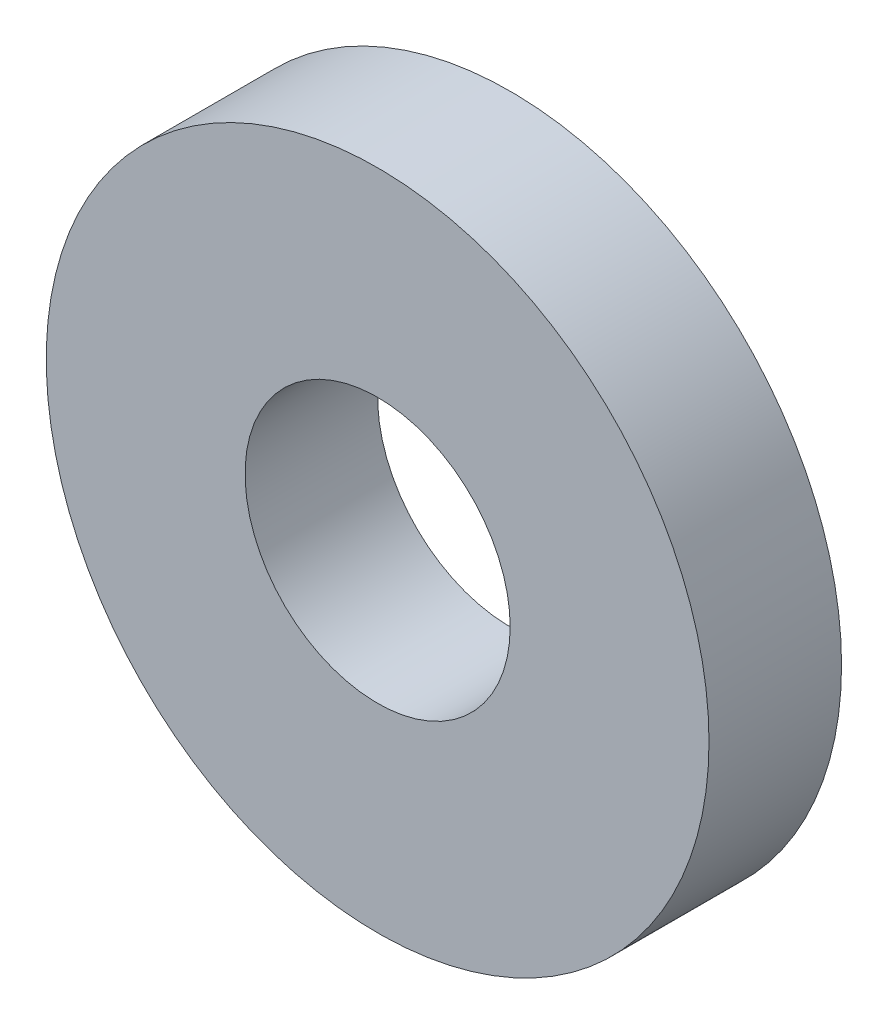
SolidWorks part; units mm, degrees
ref_plane "Front Plane" through (0, 0, 0) normal (0, 0, 1) x (1, 0, 0)
ref_plane "Top Plane" through (0, 0, 0) normal (0, 1, 0) x (1, 0, 0)
ref_plane "Right Plane" through (0, 0, 0) normal (1, 0, 0) x (0, 0, -1)
sketch "Sketch1" plane through (0, 0, 0) normal (0, 0, 1) x (1, 0, 0)
  circle A0 centre (0, 0) radius 25
  circle A1 centre (0, 0) radius 10
extrude "Boss-Extrude1" add sketch "Sketch1" along normal blind 10
